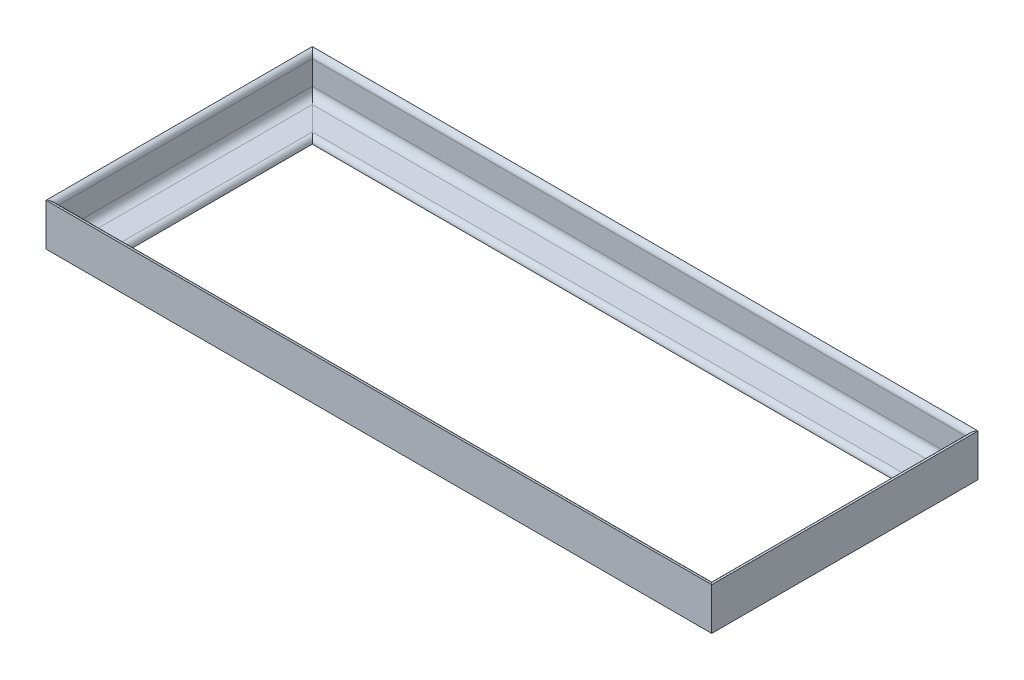
SolidWorks part; units mm, degrees
material "Fundición gris (SN)"
ref_plane "Alzado" through (0, 0, 0) normal (0, 0, 1) x (1, 0, 0)
ref_plane "Planta" through (0, 0, 0) normal (0, 1, 0) x (1, 0, 0)
ref_plane "Vista lateral" through (0, 0, 0) normal (1, 0, 0) x (0, 0, -1)
sketch "Croquis1" plane through (0, 0, 0) normal (0, 1, 0) x (1, 0, 0)
  line L1 (200, -80) -> (-200, -80)
  line L2 (200, -80) -> (200, 80)
  line L3 (200, 80) -> (-200, 80)
  line L4 (-200, -80) -> (-200, 80)
  line L5 (200, -80) -> (-200, 80) construction
  line L6 (200, 80) -> (-200, -80) construction
  point P0 (0, 0)
  dimension "D1" = 160
  dimension "D2" = 400
other "Hierro angular 1 X 1 X 0.125(1)"
ref_plane "Plano1" through (200, 0, -80) normal (-1, 0, 0) x (0, 0, 1)
sketch "Sketch1" plane through (200, 0, -80) normal (-1, 0, 0) x (0, 0, 1)
  line L0 (0, 0) -> (0, 25.4)
  line L1 (0, 25.4) -> (0.0051, 25.4)
  line L2 (3.175, 22.2301) -> (3.175, 7.9375)
  line L3 (7.9375, 3.175) -> (22.2301, 3.175)
  line L4 (25.4, 0.0051) -> (25.4, 0)
  line L5 (25.4, 0) -> (0, 0)
  arc A0 (25.4, 0.0051) -> (22.2301, 3.175) centre (22.2301, 0.0051) ccw
  arc A1 (0.0051, 25.4) -> (3.175, 22.2301) centre (0.0051, 22.2301) cw
  arc A2 (7.9375, 3.175) -> (3.175, 7.9375) centre (7.9375, 7.9375) cw
  point P10 (12.7, 0)
  point P14 (0, 12.7)
  point P15 (3.175, 12.7)
  point P16 (12.7, 3.175)
  point P17 (3.175, 25.4)
  point P18 (25.4, 3.175)
  point P19 (0, 0)
  dimension "D2" = 0.0051
  dimension "Radius_1" = 4.7625
  dimension "D1" = 3.175
  dimension "H_leg" = 25.4
